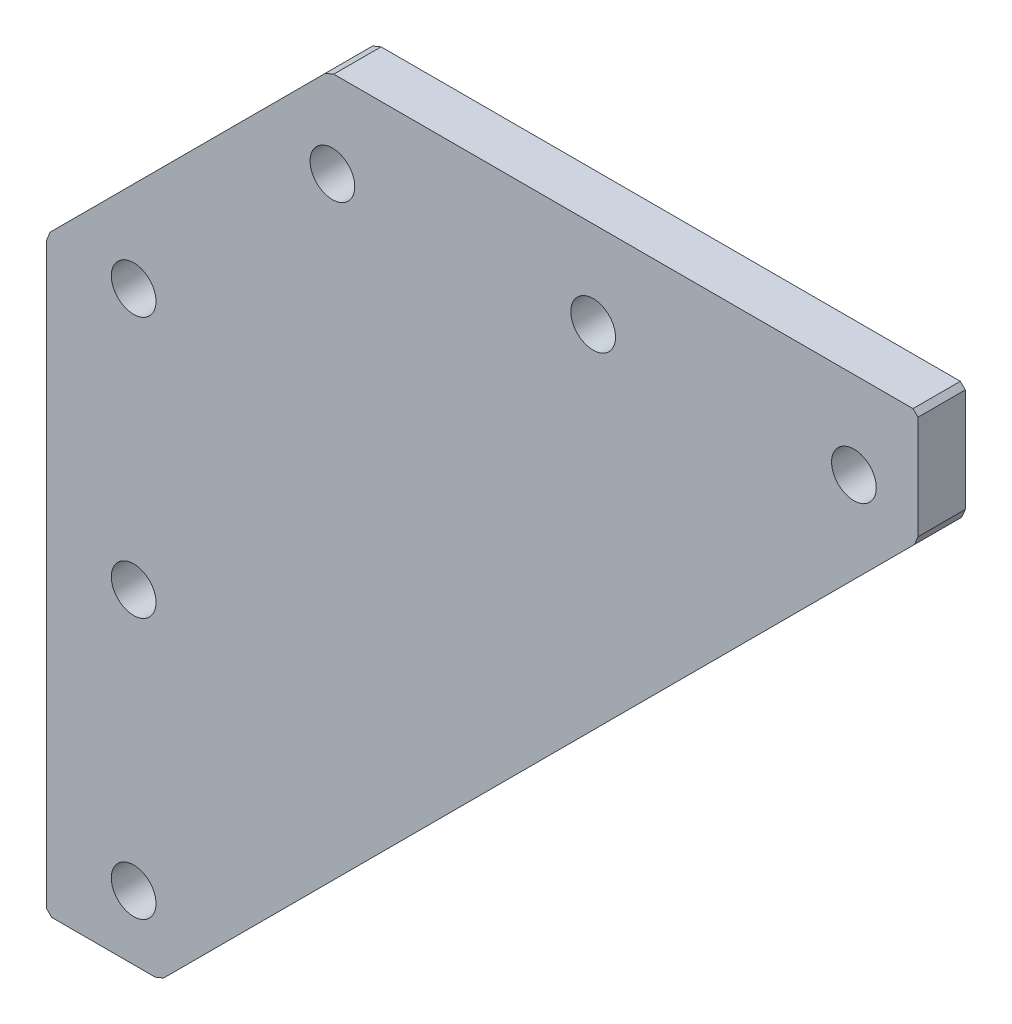
SolidWorks part; units mm, degrees
material "6061-T6 (SS)"
ref_plane "Front Plane" through (0, 0, 0) normal (0, 0, 1) x (1, 0, 0)
ref_plane "Top Plane" through (0, 0, 0) normal (0, 1, 0) x (1, 0, 0)
ref_plane "Right Plane" through (0, 0, 0) normal (1, 0, 0) x (0, 0, -1)
sketch "Sketch1" plane through (0, 0, 0) normal (0, 0, 1) x (1, 0, 0)
  line L1 (-17.5, -157.849) -> (5.3401, -157.849)
  line L2 (5.3401, -157.849) -> (157.849, -5.3401)
  line L3 (157.849, -5.3401) -> (157.849, 17.5)
  line L4 (157.849, 17.5) -> (39.2678, 17.5)
  line L6 (144.9569, 0) -> (157.849, 0) construction
  line L9 (0, -144.9569) -> (0, -157.849) construction
  line L10 (0, -40) -> (40, -40) construction
  line L11 (0, 0) -> (40, 0) construction
  line L12 (40, 0) -> (40, -40) construction
  line L13 (144.9569, 0) -> (40, 0) construction
  line L14 (0, 0) -> (0, -40) construction
  line L15 (0, -40) -> (0, -144.9569) construction
  line L16 (-17.5, -39.2678) -> (-17.5, -157.849)
  line L17 (-17.5, -39.2678) -> (39.2678, 17.5)
  line L18 (0, -40) -> (-9.1161, -30.8839) construction
  line L19 (0, -20) -> (20, 0) construction
  line L20 (144.9569, 0) -> (154.073, -9.1161) construction
  dimension "D1" = 40
  dimension "D2" = 104.9569
  dimension "D3" = 100
  dimension "D4" = 17.5
  dimension "D5" = 2.5
extrude "Boss-Extrude1" add sketch "Sketch1" along normal mid plane 9.525
hole_wizard "M8 Clearance Hole1" positions "Sketch2" profile "Sketch3" hole size "M8" standard "ANSI Metric" end condition up to next
sketch "Sketch2" plane through (0, 0, 4.7625) normal (0, 0, 1) x (1, 0, 0)
  line L2 (144.9569, 0) -> (40, 0) construction
  line L3 (0, -40) -> (0, -144.9569) construction
  point P0 (0, -92.4784)
  point P3 (144.9569, 0)
  point P6 (92.4784, 0)
  point P10 (0, -40)
  point P14 (0, -144.9569)
  point P17 (40, 0)
sketch "Sketch3" plane through (0, -92.4784, 4.7625) normal (1, 0, 0) x (0, -1, 0)
  line L0 (0, 0) -> (0, 9.525)
  line L1 (0, 9.525) -> (4.5, 9.525)
  line L2 (4.5, 9.525) -> (4.5, 0)
  line L5 (4.5, 0) -> (0, 0)
  line L11 (0, -6.35) -> (0, 107.95) construction
  dimension "Thru Hole Dia." = 9
  dimension "Thru Hole Depth" = 9.525
chamfer "Chamfer1" distance 1 distance2 1 6 edges at (157.849, 17.5, 0) (-17.5, -157.849, 0) (157.849, -5.3401, 0) (5.3401, -157.849, 0) (-17.5, -39.2678, 0) (39.2678, 17.5, 0)
